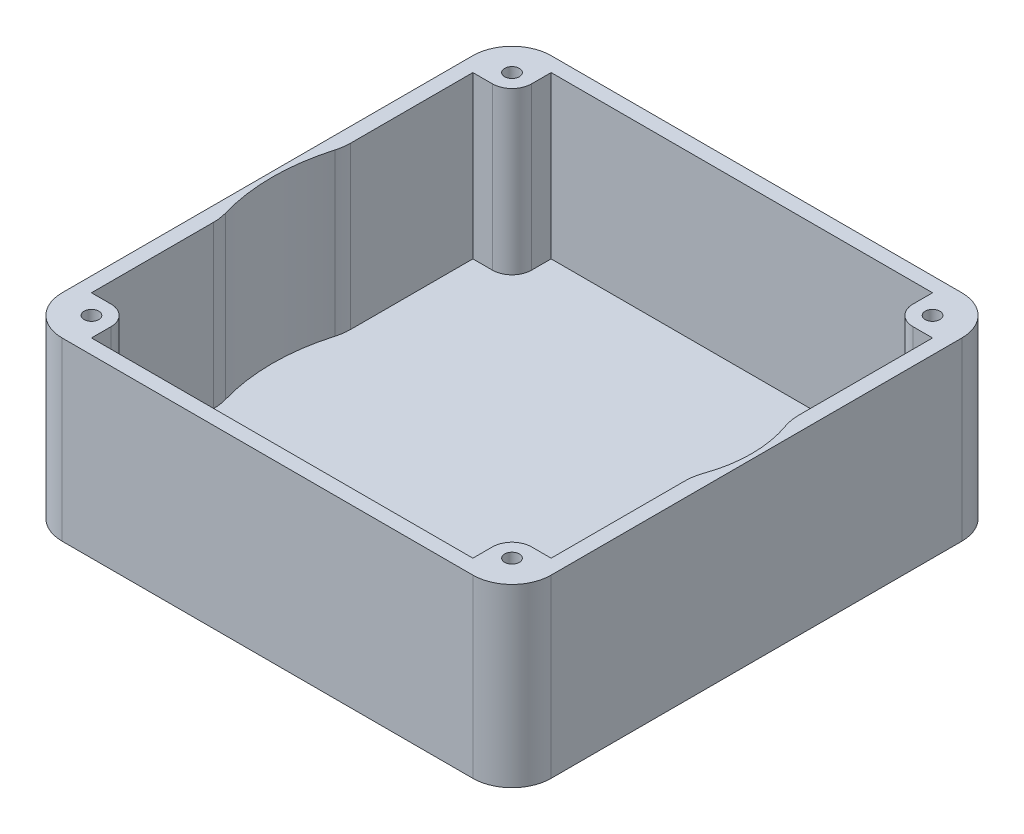
SolidWorks part; units mm, degrees
ref_plane "Спереди" through (0, 0, 0) normal (0, 0, 1) x (1, 0, 0)
ref_plane "Сверху" through (0, 0, 0) normal (0, 1, 0) x (1, 0, 0)
ref_plane "Справа" through (0, 0, 0) normal (1, 0, 0) x (0, 0, -1)
sketch "Эскиз1" plane through (0, 0, 0) normal (0, 1, 0) x (1, 0, 0)
  line L0 (0, 50) -> (100, 50) construction
  line L17 (0, 0) -> (100, 0)
  line L18 (0, 0) -> (0, 100)
  line L19 (0, 100) -> (100, 100)
  line L20 (100, 0) -> (100, 100)
  line L21 (50, 100) -> (50, 0) construction
  dimension "D1" = 100
  dimension "D2" = 100
extrude "Бобышка-Вытянуть1" add sketch "Эскиз1" along normal blind 3
sketch "Эскиз4" plane through (0, 3, 0) normal (0, 1, 0) x (1, 0, 0)
  line L0 (97, 97) -> (3, 97)
  line L1 (3, 97) -> (3, 64)
  line L2 (3, 3) -> (97, 3)
  line L3 (97, 3) -> (97, 38.3381)
  line L4 (0, 100) -> (0, 0)
  line L5 (0, 0) -> (100, 0)
  line L6 (100, 0) -> (100, 100)
  line L7 (100, 100) -> (0, 100)
  line L8 (0, 100) -> (0, 0)
  line L9 (0, 0) -> (100, 0)
  line L10 (100, 0) -> (100, 100)
  line L11 (100, 100) -> (0, 100)
  line L12 (0, 50) -> (100, 50) construction
  line L13 (3, 36) -> (3, 3)
  line L14 (3, 97) -> (3, 3) construction
  line L15 (97, 61.6619) -> (97, 97)
  line L16 (97, 3) -> (97, 97) construction
  arc A0 (2.6, 61.2) -> (2.6, 38.8) centre (41, 50) ccw
  arc A1 (97.5714, 41.6701) -> (97.5714, 58.3299) centre (74, 50) ccw
  arc A2 (97.5714, 58.3299) -> (97, 61.6619) centre (107, 61.6619) cw
  arc A3 (97.5714, 41.6701) -> (97, 38.3381) centre (107, 38.3381) ccw
  arc A4 (2.6, 38.8) -> (3, 36) centre (-7, 36) cw
  arc A5 (2.6, 61.2) -> (3, 64) centre (-7, 64) ccw
  point P12 (1, 50)
  point P16 (99, 50)
  point P20 (97, 59.798)
  point P25 (3, 37.51)
  dimension "D4" = 80
  dimension "D6" = 50
  dimension "D7" = 10
  dimension "D3" = 1
  dimension "D5" = 1
  dimension "D1" = 0
  dimension "D2" = 3
extrude "Бобышка-Вытянуть4" add sketch "Эскиз4" along normal blind 33
fillet "Скругление3" radius 8 4 edges at (100, 18, -100) (100, 18, 0) (0, 18, 0) (0, 18, -100)
sketch "Эскиз7" plane through (0, 3, 0) normal (0, 1, 0) x (1, 0, 0)
  line L0 (3, 97) -> (3, 64) construction
  line L2 (97, 97) -> (3, 97) construction
  line L6 (50, 97) -> (50, 3) construction
  line L7 (3, 3) -> (97, 3) construction
  line L8 (0, 50) -> (100, 50) construction
  line L9 (0, 92) -> (0, 8) construction
  line L10 (100, 8) -> (100, 92) construction
  line L15 (3, 89) -> (3, 97)
  line L16 (3, 97) -> (11, 97)
  line L17 (7, 89) -> (3, 89)
  line L18 (3, 97) -> (3, 64) construction
  line L19 (11, 93) -> (11, 97)
  line L20 (97, 97) -> (3, 97) construction
  line L21 (89, 93) -> (89, 97)
  line L22 (93, 89) -> (97, 89)
  line L23 (97, 97) -> (89, 97)
  line L24 (97, 89) -> (97, 97)
  line L25 (97, 11) -> (97, 3)
  line L26 (97, 3) -> (89, 3)
  line L27 (93, 11) -> (97, 11)
  line L28 (89, 7) -> (89, 3)
  line L29 (11, 7) -> (11, 3)
  line L30 (7, 11) -> (3, 11)
  line L31 (3, 3) -> (11, 3)
  line L32 (3, 11) -> (3, 3)
  arc A0 (7, 89) -> (11, 93) centre (7, 93) ccw
  circle A18 centre (7, 93) radius 1.5
  circle A19 centre (93, 93) radius 1.5
  arc A20 (93, 89) -> (89, 93) centre (93, 93) cw
  arc A21 (93, 11) -> (89, 7) centre (93, 7) ccw
  circle A22 centre (93, 7) radius 1.5
  circle A23 centre (7, 7) radius 1.5
  arc A24 (7, 11) -> (11, 7) centre (7, 7) cw
extrude "Бобышка-Вытянуть6" add sketch "Эскиз7" along normal up to surface (33 mm away) up to face at (50, 36, -50)
